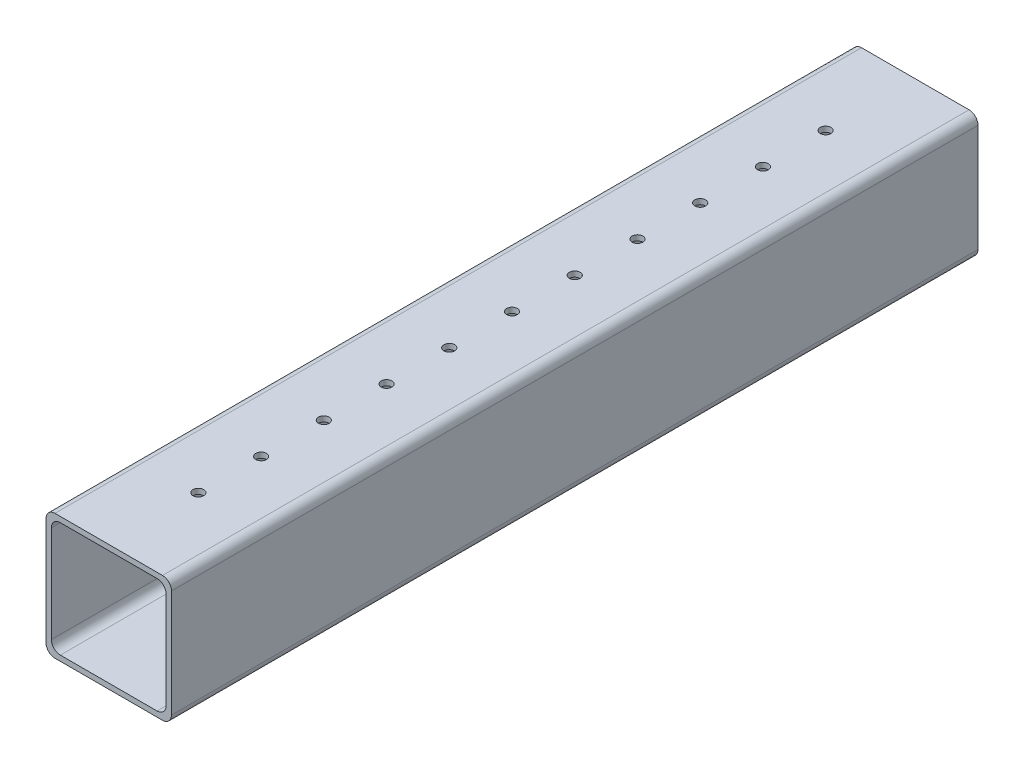
SolidWorks part; units mm, degrees
ref_plane "Front Plane" through (0, 0, 0) normal (0, 0, 1) x (1, 0, 0)
ref_plane "Top Plane" through (0, 0, 0) normal (0, 1, 0) x (1, 0, 0)
ref_plane "Right Plane" through (0, 0, 0) normal (1, 0, 0) x (0, 0, -1)
sketch "Sketch1" plane through (0, 0, 0) normal (0, 0, 1) x (1, 0, 0)
  line L0 (3, 67) -> (67, 67)
  line L1 (0, 0) -> (70, 0)
  line L2 (0, 0) -> (0, 70)
  line L3 (0, 70) -> (70, 70)
  line L4 (70, 0) -> (70, 70)
  line L5 (67, 3) -> (67, 67)
  line L6 (3, 3) -> (67, 3)
  line L7 (3, 3) -> (3, 67)
  dimension "D1" = 70
  dimension "D2" = 70
  dimension "D3" = 3
extrude "Boss-Extrude1" add sketch "Sketch1" along normal blind 450
fillet "Fillet1" radius 5 8 edges at (67, 67, 225) (0, 70, 225) (0, 0, 225) (67, 3, 225) (70, 0, 225) (3, 3, 225) (3, 67, 225) (70, 70, 225)
sketch "Sketch3" plane through (0, 0, 0) normal (0, -1, 0) x (1, 0, 0)
  line L0 (70, 450) -> (70, 0) construction
  line L1 (5, 450) -> (65, 450) construction
  circle A0 centre (35, 225) radius 3
  dimension "D2" = 6
  dimension "D1" = 35
  dimension "D3" = 225
extrude "Cut-Extrude2" cut sketch "Sketch3" against normal blind 173
pattern_linear "LPattern1" count 6 spacing 35 along (0, 0, -1) count 6 spacing 35 along (0, 0, 1) of "Cut-Extrude2"
